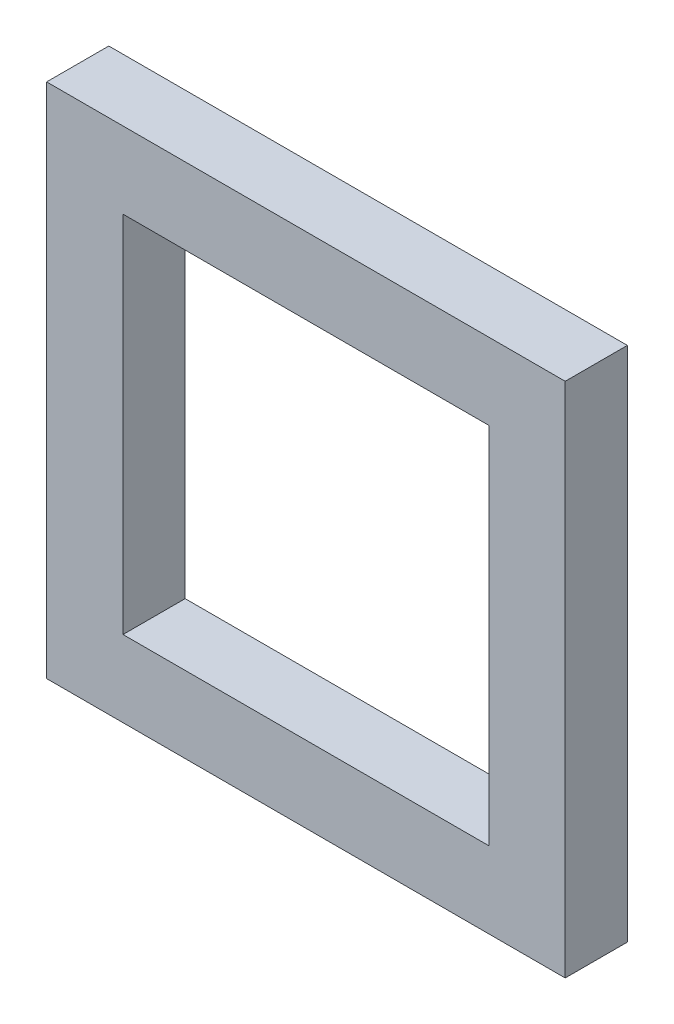
SolidWorks part; units mm, degrees
ref_plane "Front Plane" through (0, 0, 0) normal (0, 0, 1) x (1, 0, 0)
ref_plane "Top Plane" through (0, 0, 0) normal (0, 1, 0) x (1, 0, 0)
ref_plane "Right Plane" through (0, 0, 0) normal (1, 0, 0) x (0, 0, -1)
sketch "Sketch1" plane through (0, 0, 0) normal (0, 0, 1) x (1, 0, 0)
  line L0 (3.302, 60.452) -> (3.302, 3.302)
  line L1 (0, 0) -> (64.008, 0)
  line L2 (0, 0) -> (0, 63.754)
  line L3 (0, 63.754) -> (3.302, 63.754)
  line L5 (3.302, 63.754) -> (60.706, 63.754)
  line L7 (3.302, 60.452) -> (60.706, 60.452)
  line L9 (60.706, 63.754) -> (64.008, 63.754)
  line L12 (64.008, 63.754) -> (64.008, 0)
  line L17 (3.302, 3.302) -> (60.706, 3.302)
  line L18 (60.706, 3.302) -> (60.706, 60.452)
  line L20 (-5.08, 68.834) -> (69.088, 68.834)
  line L21 (-5.08, 68.834) -> (-5.08, -5.08)
  line L22 (-5.08, -5.08) -> (69.088, -5.08)
  line L23 (69.088, 68.834) -> (69.088, -5.08)
  line L24 (5.842, 57.912) -> (58.166, 57.912)
  line L25 (5.842, 57.912) -> (5.842, 5.842)
  line L26 (5.842, 5.842) -> (58.166, 5.842)
  line L27 (58.166, 57.912) -> (58.166, 5.842)
  dimension "D1" = 3.302
  dimension "D2" = 3.302
  dimension "D3" = 63.754
  dimension "D4" = 57.404
  dimension "D5" = 3.302
  dimension "D6" = 3.302
  dimension "D7" = 3.302
  dimension "D8" = 5.08
  dimension "D9" = 5.08
  dimension "D10" = 5.08
  dimension "D11" = 5.08
  dimension "D12" = 2.54
  dimension "D13" = 2.54
  dimension "D14" = 2.54
  dimension "D15" = 2.54
extrude "Boss-Extrude1" add sketch "Sketch1" along normal blind 6.35 contours L23 L20 L21 L22 L9 L12 L1 L2 L3 L5 | L17 L18 L7 L0 | L27 L24 L25 L26
sketch "Sketch2" plane through (0, 0, 6.35) normal (0, 0, 1) x (1, 0, 0)
  line L1 (-5.08, 68.834) -> (69.088, 68.834)
  line L2 (-5.08, 68.834) -> (-5.08, -5.08)
  line L3 (-5.08, -5.08) -> (69.088, -5.08)
  line L4 (69.088, 68.834) -> (69.088, -5.08)
  line L13 (5.842, 57.912) -> (58.166, 57.912)
  line L14 (5.842, 57.912) -> (5.842, 5.842)
  line L15 (5.842, 5.842) -> (58.166, 5.842)
  line L16 (58.166, 57.912) -> (58.166, 5.842)
extrude "Boss-Extrude2" add sketch "Sketch2" along normal blind 2.54
